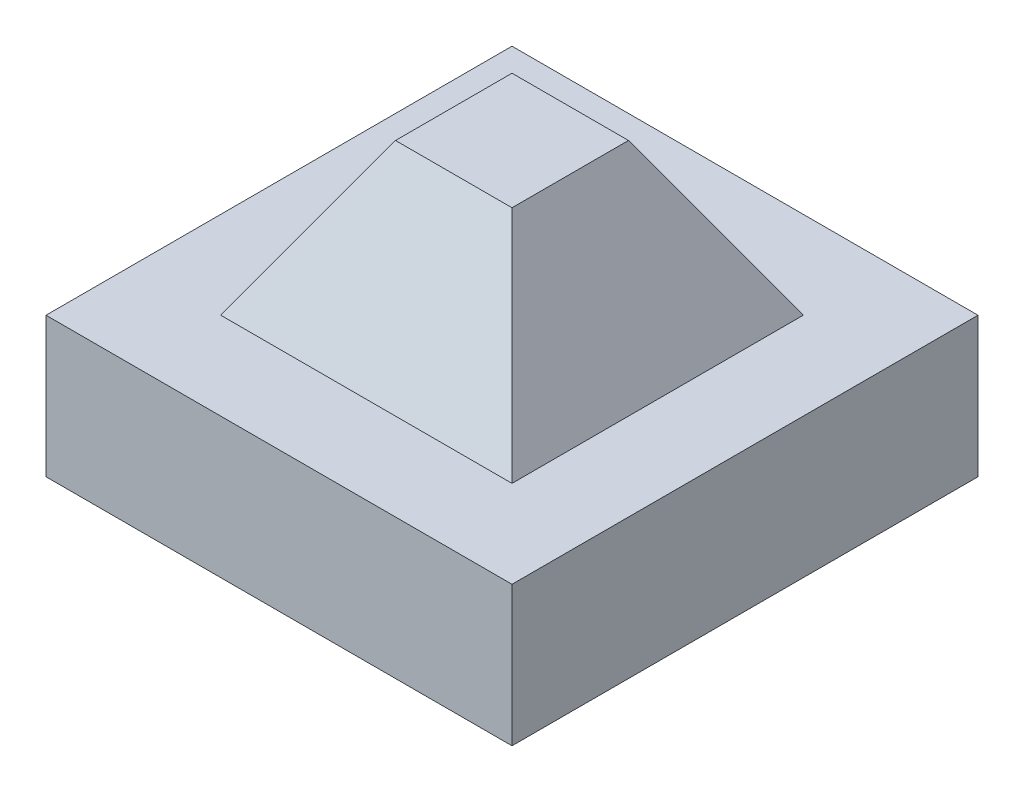
SolidWorks part; units mm, degrees
ref_plane "前视基准面" through (0, 0, 0) normal (0, 0, 1) x (1, 0, 0)
ref_plane "上视基准面" through (0, 0, 0) normal (0, 1, 0) x (1, 0, 0)
ref_plane "右视基准面" through (0, 0, 0) normal (1, 0, 0) x (0, 0, -1)
sketch "草图1" plane through (0, 0, 0) normal (0, 1, 0) x (1, 0, 0)
  line L1 (-400, -400) -> (400, -400)
  line L2 (-400, -400) -> (-400, 400)
  line L3 (-400, 400) -> (400, 400)
  line L4 (400, -400) -> (400, 400)
  line L5 (-400, -400) -> (400, 400) construction
  line L6 (-400, 400) -> (400, -400) construction
  point P0 (0, 0)
  dimension "D1" = 800
  dimension "D2" = 800
extrude "凸台-拉伸1" add sketch "草图1" along normal blind 500
sketch "草图2" plane through (-400, 0, 0) normal (-1, 0, 0) x (0, 0, 1)
  line L0 (-400, 240.1924) -> (-250, 240.1924)
  line L1 (-400, 500) -> (-400, 0) construction
  line L2 (-250, 240.1924) -> (-100, 500)
  line L3 (-400, 500) -> (400, 500) construction
  line L4 (-100, 500) -> (-400, 500)
  line L5 (-400, 500) -> (-400, 240.1924)
  line L6 (0, 0) -> (0, 500) construction
  line L7 (-400, 0) -> (400, 0) construction
  line L8 (250, 240.1924) -> (100, 500)
  line L9 (100, 500) -> (400, 500)
  line L10 (400, 500) -> (400, 240.1924)
  line L11 (400, 240.1924) -> (250, 240.1924)
  dimension "D1" = 150
  dimension "D2" = 60
  dimension "D3" = 100
extrude "切除-拉伸1" cut sketch "草图2" against normal through all both and the other way through all
sketch "草图3" plane through (0, 0, -400) normal (0, 0, -1) x (-1, 0, 0)
  line L0 (0, 0) -> (0, 500) construction
  line L1 (-400, 500) -> (400, 500) construction
  line L2 (-400, 240.1924) -> (-250, 240.1924)
  line L3 (-400, 240.1924) -> (400, 240.1924) construction
  line L4 (-250, 240.1924) -> (-100, 500)
  line L5 (-100, 500) -> (-400, 500)
  line L6 (-400, 500) -> (-400, 240.1924)
  line L7 (250, 240.1924) -> (100, 500)
  line L8 (400, 240.1924) -> (250, 240.1924)
  line L9 (400, 500) -> (400, 240.1924)
  line L10 (100, 500) -> (400, 500)
  dimension "D1" = 60
  dimension "D2" = 100
extrude "切除-拉伸2" cut sketch "草图3" against normal through all both and the other way through all
sketch "草图4" plane through (0, 500, 0) normal (0, 1, 0) x (1, 0, 0)
  point P0 (0, 0)
